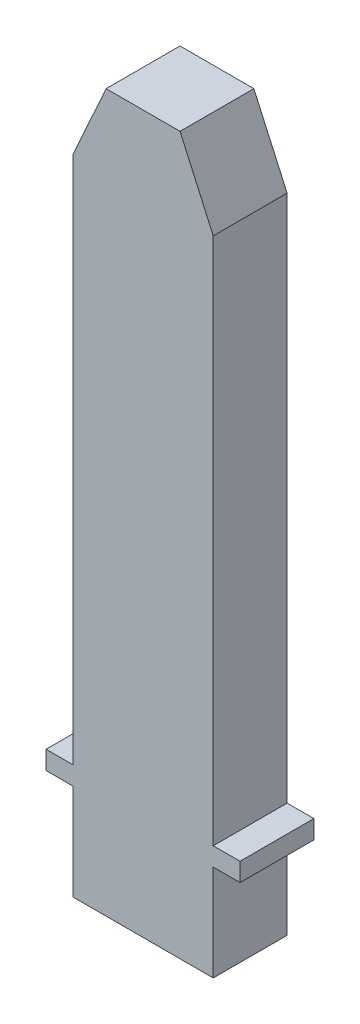
SolidWorks part; units mm, degrees
ref_plane "Front Plane" through (0, 0, 0) normal (0, 0, 1) x (1, 0, 0)
ref_plane "Top Plane" through (0, 0, 0) normal (0, 1, 0) x (1, 0, 0)
ref_plane "Right Plane" through (0, 0, 0) normal (1, 0, 0) x (0, 0, -1)
sketch "Sketch1" plane through (0, 0, 0) normal (0, 0, 1) x (1, 0, 0)
  line L0 (1.9, 0) -> (2.625, 0)
  line L2 (-1.9, 14.3) -> (-1.9, 0)
  line L4 (1.9, 14.3) -> (1.9, 0)
  line L5 (-2.625, 0) -> (-1.9, 0)
  line L6 (-2.625, 0) -> (-2.625, -0.5)
  line L7 (-2.625, -0.5) -> (-1.9, -0.5)
  line L8 (2.625, 0) -> (2.625, -0.5)
  line L9 (1.9, -0.5) -> (2.625, -0.5)
  line L11 (-1.9, -0.5) -> (-1.9, -3.1)
  line L12 (-1.9, -3.1) -> (1.9, -3.1)
  line L13 (1.9, -0.5) -> (1.9, -3.1)
  line L14 (-1, 16.3) -> (1, 16.3)
  line L15 (-1.9, 14.3) -> (-1, 16.3)
  line L16 (1, 16.3) -> (1.9, 14.3)
  point P9 (2.625, -0.25)
  dimension "D2" = 3.8
  dimension "D3" = 1.9
  dimension "D5" = 5.25
  dimension "D6" = 2.625
  dimension "D1" = 2.6
  dimension "D7" = 1.9
  dimension "D8" = 1.9
  dimension "D9" = 0.25
  dimension "D10" = 0.5
  dimension "D11" = 2
  dimension "D13" = 0.9
  dimension "D14" = 3.8
  dimension "D4" = 14.3
  dimension "D12" = 16.3
extrude "Boss-Extrude1" add sketch "Sketch1" along normal blind 2
ref_plane "Plane1" through (0, -4.9, 0) normal (0, -1, 0) x (-1, 0, 0)
ref_plane "Plane2" through (0, 0, 1.8) normal (0, 0, 1) x (1, 0, 0)
ref_plane "Plane3" through (1.8, 0, 0) normal (1, 0, 0) x (0, 0, -1)
equation "\"D3@Sketch1\"=\"D2@Sketch1\"/2"
equation "\"D6@Sketch1\"=\"D5@Sketch1\"/2"
